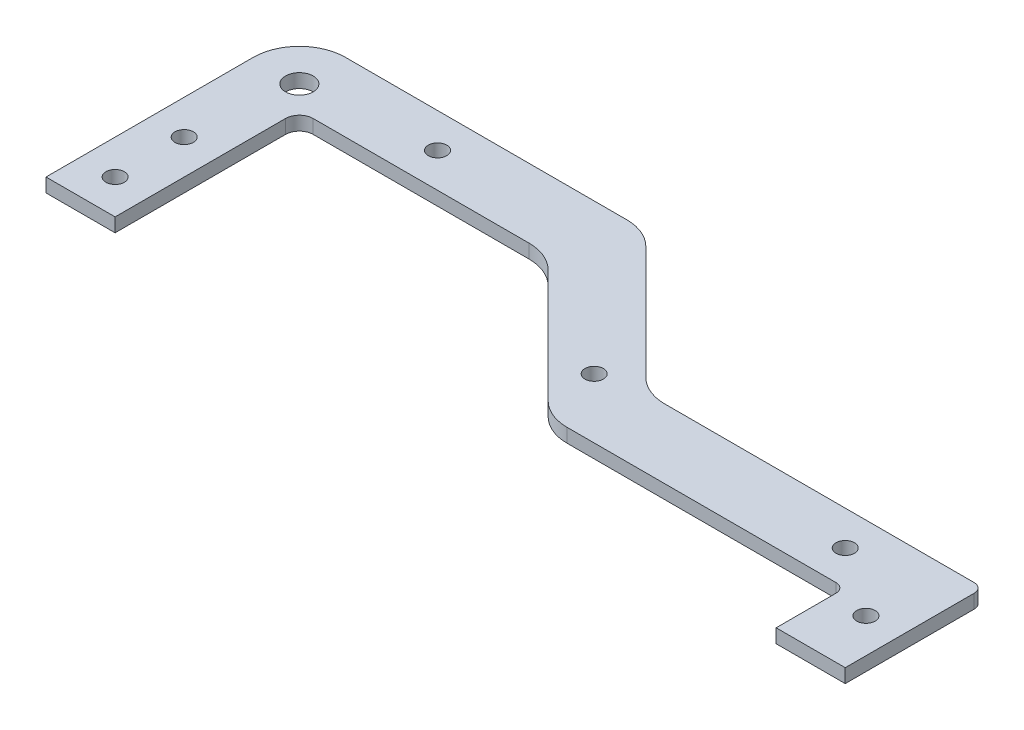
SolidWorks part; units mm, degrees
material "Thornel Mat VMA"
ref_plane "前视基准面" through (0, 0, 0) normal (0, 0, 1) x (1, 0, 0)
ref_plane "上视基准面" through (0, 0, 0) normal (0, 1, 0) x (1, 0, 0)
ref_plane "右视基准面" through (0, 0, 0) normal (1, 0, 0) x (0, 0, -1)
sketch "草图1" plane through (0, 0, 0) normal (0, 1, 0) x (1, 0, 0)
  line L1 (-55, 0) -> (-40, 0)
  line L12 (-204, 45.5) -> (-150, 45.5)
  line L28 (-209, 60.5) -> (-143.7868, 60.5)
  line L31 (-150, 45.5) -> (-119.5, 15)
  line L37 (-219, 50.5) -> (-219, 5.5)
  line L39 (0, 0) -> (0, 76.5) construction
  line L64 (-113.2868, 30) -> (-143.7868, 60.5)
  line L66 (-219, 5.5) -> (-204, 5.5)
  line L68 (-204, 5.5) -> (-204, 45.5)
  line L70 (-55, 0) -> (-55, 15)
  line L74 (-40, 0) -> (-40, 30)
  line L80 (-119.5, 15) -> (-55, 15)
  line L82 (-113.2868, 30) -> (-40, 30)
  arc A0 (-209, 60.5) -> (-219, 50.5) centre (-209, 50.5) ccw
  point P2 (-204, 45.5)
  point P8 (-202.77, 45.5)
  dimension "D3" = 110
  dimension "D4" = 60.5
  dimension "D5" = 179
  dimension "D6" = 15
  dimension "D7" = 10
  dimension "D10" = 15
  dimension "D12" = 15
  dimension "D8" = 40
  dimension "D13" = 30
  dimension "D17" = 55
  dimension "D18" = 135
  dimension "D19" = 15
  dimension "D22" = 15
extrude "凸台-拉伸1" add sketch "草图1" along normal blind 3
sketch "草图2" plane through (0, 3, 0) normal (0, 1, 0) x (1, 0, 0)
  line L0 (-143.7868, 60.5) -> (-209, 60.5) construction
  line L1 (-55, 0) -> (-40, 0) construction
  line L3 (-47.5, 12) -> (-47.5, 0) construction
  line L6 (-219, 50.5) -> (-219, 5.5) construction
  line L7 (-219, 5.5) -> (-204, 5.5) construction
  line L8 (-40, 30) -> (-113.2868, 30) construction
  line L14 (-55, 15) -> (-55, 0) construction
  circle A10 centre (-47.5, 12) radius 2
  circle A18 centre (-211.5, 13) radius 2
  circle A19 centre (-211.5, 28) radius 2
  circle A39 centre (-209, 50.5) radius 3
  circle A41 centre (-181.5, 53) radius 2
  circle A42 centre (-122.5, 28) radius 2
  circle A47 centre (-62.5, 22.5) radius 2
  point P29 (-211.5, 5.5)
  dimension "D3" = 12
  dimension "D4" = 10
  dimension "D7" = 15
  dimension "D9" = 4
  dimension "D10" = 7.5
  dimension "D11" = 37.5
  dimension "D6" = 7.5
  dimension "D19" = 4
  dimension "D23" = 7.5
  dimension "D13" = 6
  dimension "D14" = 60
  dimension "D15" = 32.5
  dimension "D5" = 7.5
  dimension "D12" = 10
extrude "切除-拉伸1" cut sketch "草图2" against normal blind 10
fillet "圆角1" radius 10 4 edges at (-150, 1.5, -45.5) (-143.7868, 1.5, -60.5) (-119.5, 1.5, -15) (-113.2868, 1.5, -30)
fillet "圆角2" radius 2 2 edges at (-40, 1.5, -30) (-55, 1.5, -15)
fillet "圆角3" radius 3 1 edges at (-204, 1.5, -45.5)
